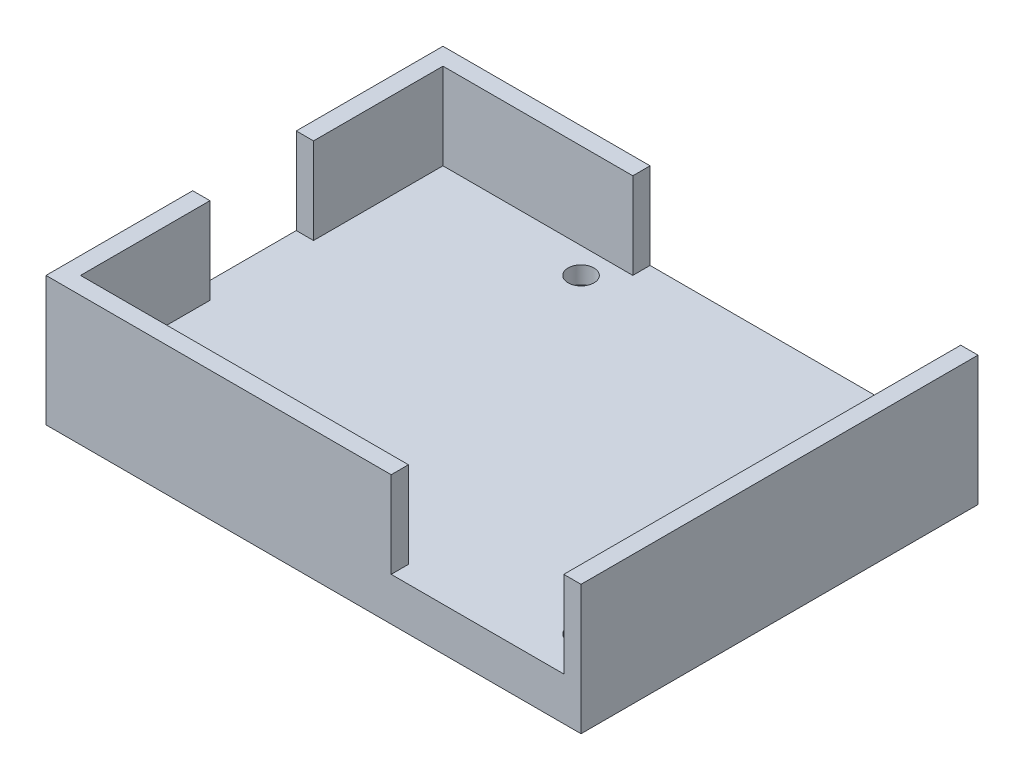
SolidWorks part; units mm, degrees
material "ABS"
ref_plane "前视基准面" through (0, 0, 0) normal (0, 0, 1) x (1, 0, 0)
ref_plane "上视基准面" through (0, 0, 0) normal (0, 1, 0) x (1, 0, 0)
ref_plane "右视基准面" through (0, 0, 0) normal (1, 0, 0) x (0, 0, -1)
sketch "草图1" plane through (0, 0, 0) normal (0, 1, 0) x (1, 0, 0)
  line L1 (-31, 23) -> (31, 23)
  line L2 (-31, 23) -> (-31, -23)
  line L3 (-31, -23) -> (31, -23)
  line L4 (31, 23) -> (31, -23)
  line L5 (-31, 23) -> (31, -23) construction
  line L6 (-31, -23) -> (31, 23) construction
  point P0 (0, 0)
  dimension "D1" = 62
  dimension "D2" = 46
extrude "凸台-拉伸1" add sketch "草图1" along normal blind 15
sketch "草图2" plane through (0, 15, 0) normal (0, 1, 0) x (1, 0, 0)
  line L1 (-29, 21) -> (29, 21)
  line L2 (-29, 21) -> (-29, -21)
  line L3 (-29, -21) -> (29, -21)
  line L4 (29, 21) -> (29, -21)
  line L5 (-29, 21) -> (29, -21) construction
  line L6 (-29, -21) -> (29, 21) construction
  point P0 (0, 0)
  dimension "D1" = 58
  dimension "D2" = 42
extrude "切除-拉伸1" cut sketch "草图2" against normal blind 10
sketch "草图3" plane through (-31, 0, 0) normal (-1, 0, 0) x (0, 0, 1)
  line L0 (-6, 25) -> (-6, 5)
  line L1 (-6, 25) -> (6, 25)
  line L2 (-6, 5) -> (6, 5)
  line L3 (6, 25) -> (6, 5)
  line L4 (-6, 25) -> (6, 5) construction
  line L5 (-6, 5) -> (6, 25) construction
  line L6 (-23, 15) -> (23, 15) construction
  point P0 (0, 15)
  point P1 (0, 15)
  dimension "D1" = 20
  dimension "D2" = 12
extrude "切除-拉伸2" cut sketch "草图3" against normal up to next
sketch "草图5" plane through (0, 0, -21) normal (0, 0, 1) x (1, 0, 0)
  line L0 (29, 5) -> (-29, 5) construction
  line L1 (29, 15) -> (-7, 15)
  line L2 (29, 15) -> (29, 5)
  line L3 (29, 5) -> (-7, 5)
  line L4 (-7, 15) -> (-7, 5)
  dimension "D1" = 36
extrude "切除-拉伸3" cut sketch "草图5" against normal up to next
sketch "草图6" plane through (0, 0, 21) normal (0, 0, -1) x (-1, 0, 0)
  line L0 (29, 5) -> (-29, 5) construction
  line L1 (-29, 15) -> (-9, 15)
  line L2 (-29, 15) -> (-29, 5)
  line L3 (-29, 5) -> (-9, 5)
  line L4 (-9, 15) -> (-9, 5)
  dimension "D1" = 20
extrude "切除-拉伸4" cut sketch "草图6" against normal up to next
sketch "草图7" plane through (0, 5, 0) normal (0, 1, 0) x (1, 0, 0)
  line L0 (-7, 21) -> (-29, 21) construction
  line L1 (29, 23) -> (26, 23) construction
  line L2 (29, 23) -> (29, 18) construction
  line L3 (29, 18) -> (26, 18) construction
  line L4 (26, 23) -> (26, 18) construction
  line L6 (26, 18) -> (-10, 18) construction
  line L7 (26, 18) -> (26, -18) construction
  line L8 (26, -18) -> (-10, -18) construction
  line L9 (-10, 18) -> (-10, -18) construction
  circle A0 centre (26, -18) radius 1.5
  circle A1 centre (26, 18) radius 1.5
  circle A2 centre (-10, 18) radius 1.5
  circle A3 centre (-10, -18) radius 1.5
  dimension "D5" = 3
  dimension "D1" = 3
  dimension "D2" = 3
  dimension "D3" = 36
  dimension "D4" = 36
extrude "切除-拉伸5" cut sketch "草图7" against normal through all
sketch "草图8" plane through (0, 0, 0) normal (0, -1, 0) x (1, 0, 0)
  circle A0 centre (-10, 18) radius 2
  circle A1 centre (26, 18) radius 2
  circle A2 centre (26, -18) radius 2
  circle A3 centre (-10, -18) radius 2
  dimension "D1" = 4
extrude "切除-拉伸6" cut sketch "草图8" against normal blind 3
